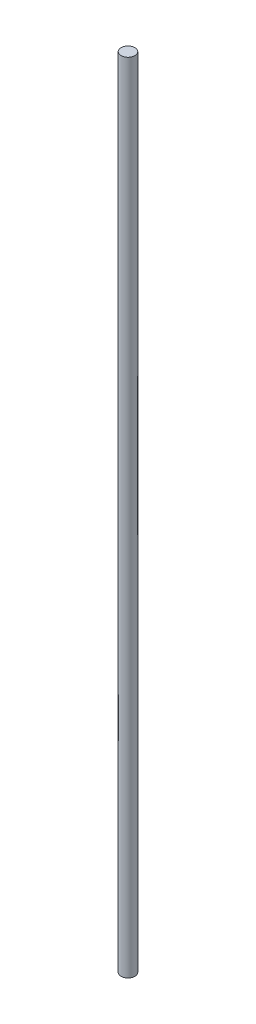
SolidWorks part; units mm, degrees
material "AISI 304"
ref_plane "前视基准面" through (0, 0, 0) normal (0, 0, 1) x (1, 0, 0)
ref_plane "上视基准面" through (0, 0, 0) normal (0, 1, 0) x (1, 0, 0)
ref_plane "右视基准面" through (0, 0, 0) normal (1, 0, 0) x (0, 0, -1)
sketch "草图1" plane through (0, 0, 0) normal (0, 1, 0) x (1, 0, 0)
  circle A0 centre (0, 0) radius 3.9688
  dimension "D1" = 7.9375
extrude "凸台-拉伸1" add sketch "草图1" along normal blind 457.2 contours A0
